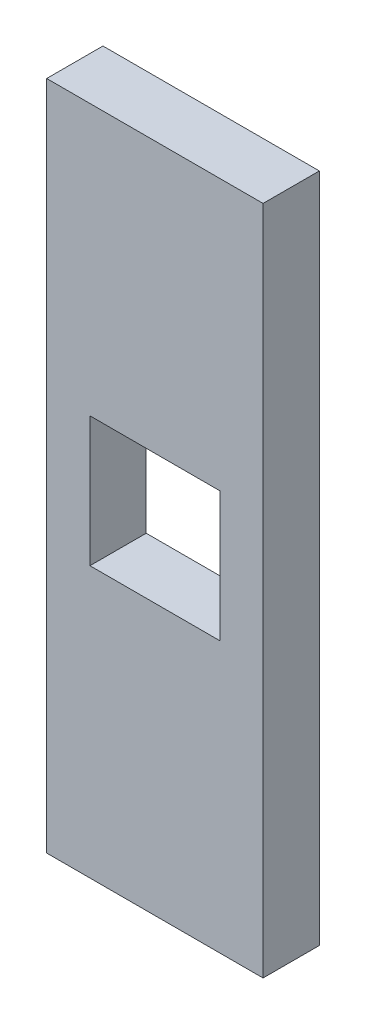
SolidWorks part; units mm, degrees
ref_plane "Front Plane" through (0, 0, 0) normal (0, 0, 1) x (1, 0, 0)
ref_plane "Top Plane" through (0, 0, 0) normal (0, 1, 0) x (1, 0, 0)
ref_plane "Right Plane" through (0, 0, 0) normal (1, 0, 0) x (0, 0, -1)
sketch "Sketch1" plane through (0, 0, 0) normal (0, 0, 1) x (1, 0, 0)
  line L0 (0, 62) -> (0, 42)
  line L1 (0, 62) -> (20, 62)
  line L2 (0, 42) -> (0, 37)
  line L3 (20, 0) -> (0, 0)
  line L4 (4, 37) -> (16, 37)
  line L5 (4, 25) -> (16, 25)
  line L6 (4, 37) -> (4, 25)
  line L7 (16, 37) -> (16, 25)
  line L8 (0, 42) -> (20, 42) construction
  line L9 (0, 37) -> (20, 37) construction
  line L10 (0, 37) -> (0, 25)
  line L11 (0, 25) -> (0, 20)
  line L12 (20, 42) -> (20, 37)
  line L13 (20, 62) -> (20, 42)
  line L14 (0, 20) -> (0, 0)
  line L15 (20, 37) -> (20, 25)
  line L16 (20, 25) -> (20, 20)
  line L17 (20, 20) -> (20, 0)
  line L18 (0, 25) -> (20, 25) construction
  line L19 (20, 20) -> (0, 20) construction
  line L20 (10, -0.0005) -> (10, 4.0956) construction
  point P18 (10, 25)
  point P20 (10, 37)
  point P21 (10, 62)
  dimension "D1" = 20
  dimension "D2" = 12
  dimension "D3" = 5
  dimension "D4" = 20
  dimension "D5" = 12
  dimension "D6" = 12
extrude "Boss-Extrude1" add sketch "Sketch1" along normal blind 5.2
